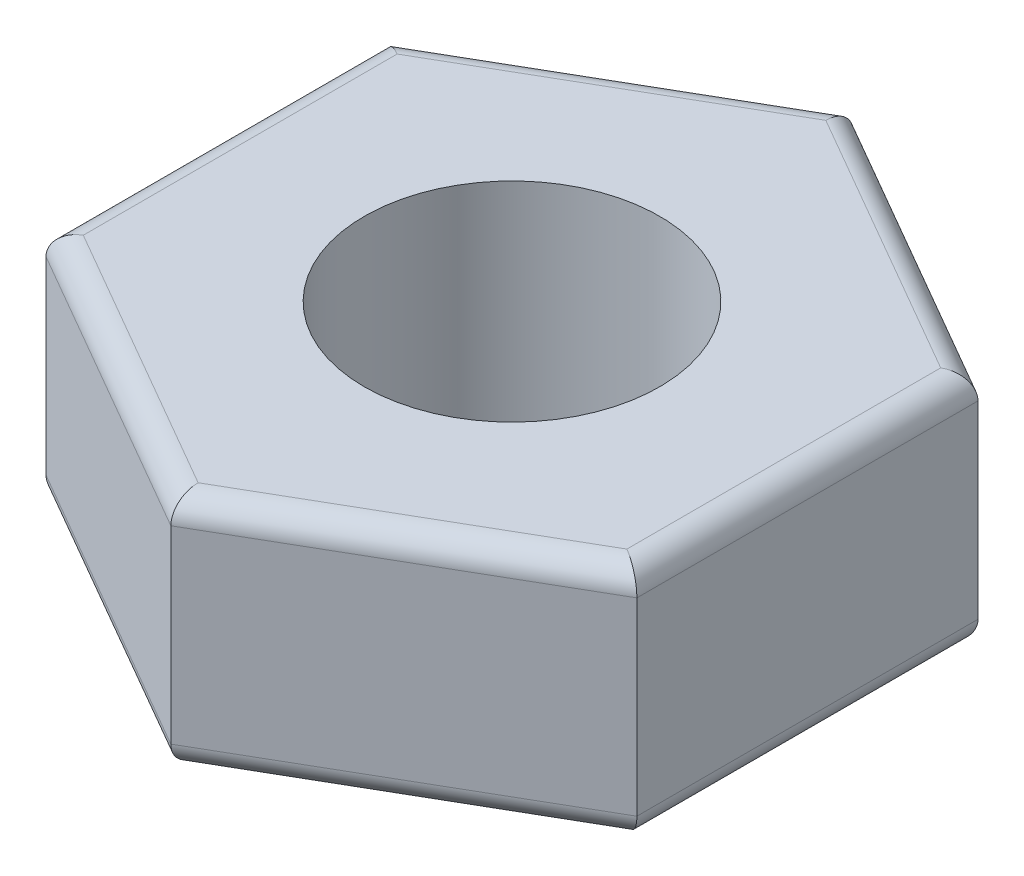
SolidWorks part; units mm, degrees
material "Nylon 101"
ref_plane "Front Plane" through (0, 0, 0) normal (0, 0, 1) x (1, 0, 0)
ref_plane "Top Plane" through (0, 0, 0) normal (0, 1, 0) x (1, 0, 0)
ref_plane "Right Plane" through (0, 0, 0) normal (1, 0, 0) x (0, 0, -1)
sketch "Sketch1" plane through (0, 0, 0) normal (0, 1, 0) x (1, 0, 0)
  line L1 (0, 5.7735) -> (-5, 2.8868)
  line L2 (-5, 2.8868) -> (-5, -2.8868)
  line L3 (-5, -2.8868) -> (0, -5.7735)
  line L4 (0, -5.7735) -> (5, -2.8868)
  line L5 (5, -2.8868) -> (5, 2.8868)
  line L6 (5, 2.8868) -> (0, 5.7735)
  circle A0 centre (0, 0) radius 2.5
  circle A1 centre (0, 0) radius 5 construction
  dimension "D1" = 5
  dimension "D2" = 10
extrude "Boss-Extrude1" add sketch "Sketch1" along normal blind 4
cosmetic thread "Cosmetic Thread1" parameters "D1"=4, "D2"=5.4
fillet "Fillet1" radius 0.4 12 edges at (2.5, 0, -4.3301) (5, 0, 0) (2.5, 0, 4.3301) (-2.5, 0, -4.3301) (-5, 0, 0) (-2.5, 0, 4.3301) (-5, 4, 0) (-2.5, 4, -4.3301) (2.5, 4, -4.3301) (5, 4, 0) (2.5, 4, 4.3301) (-2.5, 4, 4.3301)
